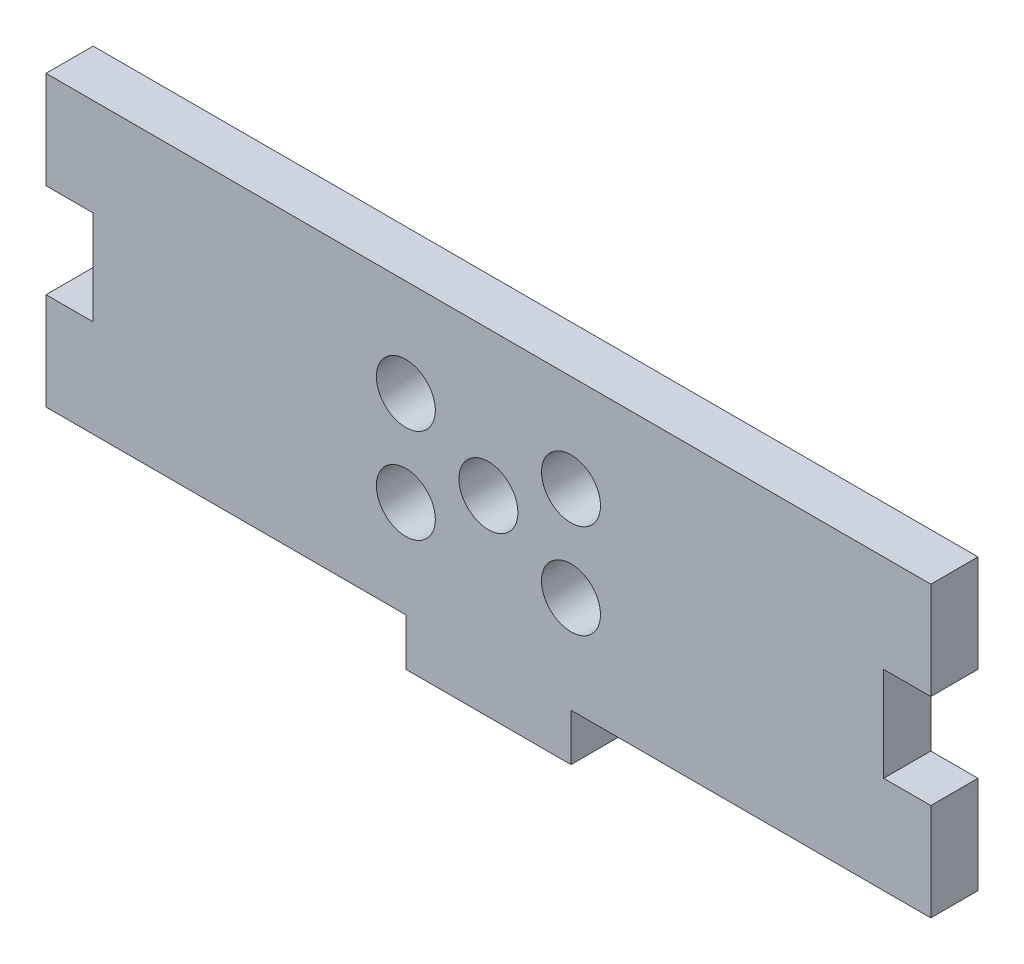
SolidWorks part; units mm, degrees
ref_plane "Alzado" through (0, 0, 0) normal (0, 0, 1) x (1, 0, 0)
ref_plane "Planta" through (0, 0, 0) normal (0, 1, 0) x (1, 0, 0)
ref_plane "Vista lateral" through (0, 0, 0) normal (1, 0, 0) x (0, 0, -1)
sketch "Croquis1" plane through (0, 0, 0) normal (0, 0, 1) x (1, 0, 0)
  line L0 (0, 0) -> (4, 0) construction
  line L1 (37.5, 12.25) -> (-37.5, 12.25)
  line L2 (37.5, 12.25) -> (37.5, 4)
  line L3 (37.5, -12.25) -> (7, -12.25)
  line L4 (-37.5, 12.25) -> (-37.5, 4)
  line L5 (37.5, 12.25) -> (-37.5, -12.25) construction
  line L6 (37.5, -12.25) -> (-37.5, 12.25) construction
  line L7 (0, 12.25) -> (0, -12.25) construction
  line L8 (4, 12.25) -> (4, -12.25) construction
  line L9 (-37.5, 4) -> (37.5, 4) construction
  line L10 (0, 0) -> (4, 4) construction
  line L11 (-33.5, 0) -> (33.5, 0) construction
  line L12 (7, 12.25) -> (7, -12.25) construction
  line L13 (-37.5, -4) -> (37.5, -4) construction
  line L14 (-37.5, 4) -> (-33.5, 4)
  line L15 (-33.5, 4) -> (-33.5, -4)
  line L16 (-33.5, -4) -> (-37.5, -4)
  line L17 (-37.5, -4) -> (-37.5, -12.25)
  line L18 (37.5, 4) -> (33.5, 4)
  line L19 (33.5, 4) -> (33.5, -4)
  line L20 (33.5, -4) -> (37.5, -4)
  line L21 (37.5, -4) -> (37.5, -12.25)
  line L22 (-7, -12.25) -> (-7, 12.25) construction
  line L23 (-7, -12.25) -> (-7, -16.25)
  line L24 (-7, -16.25) -> (7, -16.25)
  line L25 (7, -16.25) -> (7, -12.25)
  line L26 (-7, -12.25) -> (-37.5, -12.25)
  circle A0 centre (0, 0) radius 2.5
  circle A3 centre (7, 4) radius 2.5
  circle A4 centre (7, -4) radius 2.5
  circle A5 centre (-7, -4) radius 2.5
  circle A6 centre (-7, 4) radius 2.5
  point P0 (0, 0)
  dimension "D1" = 7
  dimension "D2" = 8
  dimension "D3" = 8.25
extrude "Saliente-Extruir1" add sketch "Croquis1" along normal blind 4
